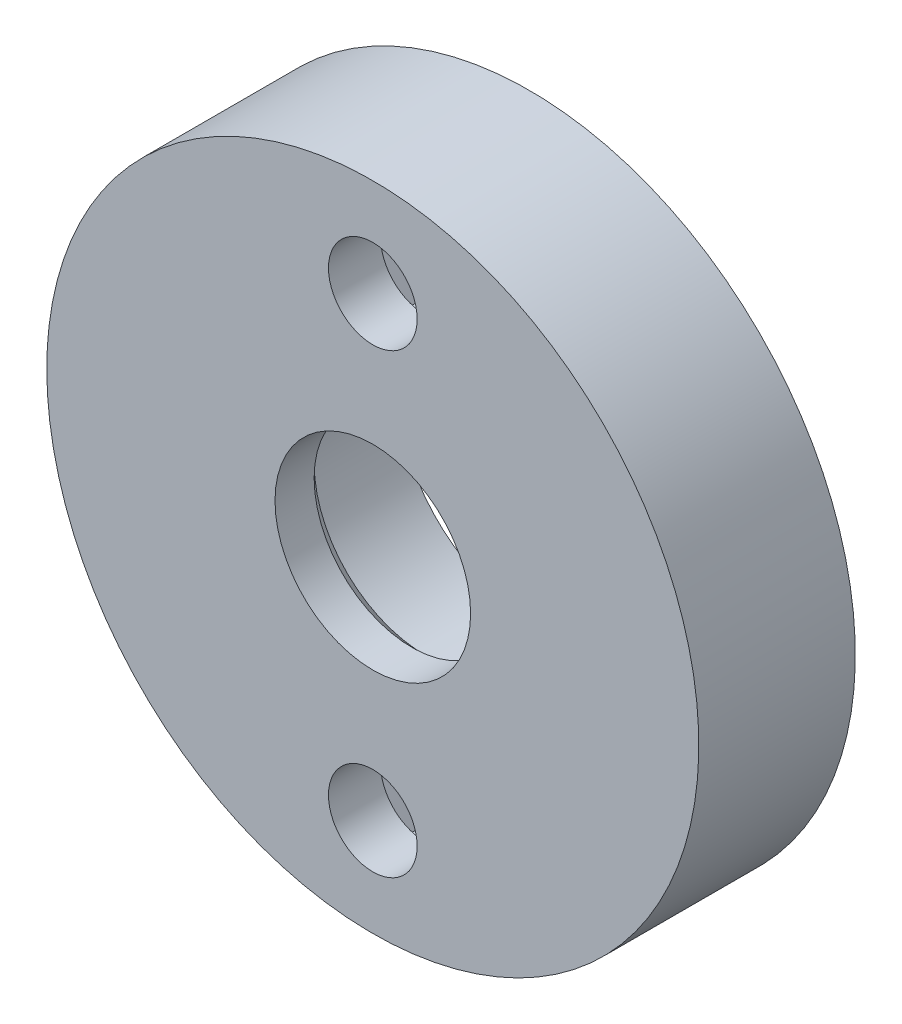
SolidWorks part; units mm, degrees
ref_plane "Plan de face" through (0, 0, 0) normal (0, 0, 1) x (1, 0, 0)
ref_plane "Plan de dessus" through (0, 0, 0) normal (0, 1, 0) x (1, 0, 0)
ref_plane "Plan de droite" through (0, 0, 0) normal (1, 0, 0) x (0, 0, -1)
sketch "Esquisse1" plane through (0, 0, 0) normal (0, 0, 1) x (1, 0, 0)
  line L0 (0, 12.5) -> (0, 0) construction
  ellipse E0 centre (0, 0) end of major axis (12.5, 0) minor radius 12.5
  dimension "D1" = 25
  dimension "D2" = 25
extrude "Boss.-Extru.1" add sketch "Esquisse1" along normal blind 6
sketch "Esquisse2" plane through (0, 0, 0) normal (0, 0, -1) x (-1, 0, 0)
  circle A0 centre (0, 0) radius 5
  dimension "D1" = 10
extrude "Enlèv. mat.-Extru.1" cut sketch "Esquisse2" against normal blind 4
sketch "Esquisse3" plane through (0, 0, 4) normal (0, 0, -1) x (-1, 0, 0)
  circle A0 centre (0, 0) radius 3.75
  dimension "D1" = 7.5
extrude "Enlèv. mat.-Extru.2" cut sketch "Esquisse3" against normal up to next
chamfer "Chanfrein1" distance 0.5 angle 45 1 edges at (-3.75, 0, 4)
sketch "Esquisse5" plane through (0, 0, 0) normal (0, 0, -1) x (-1, 0, 0)
  line L0 (0, 5) -> (0, 12.5) construction
  line L1 (-3.1177, -8.75) -> (-1.5588, -11.45)
  line L2 (3.1177, 8.75) -> (1.5588, 11.45)
  line L3 (1.5588, 11.45) -> (-1.5588, 11.45)
  line L4 (-1.5588, 11.45) -> (-3.1177, 8.75)
  line L5 (-3.1177, 8.75) -> (-1.5588, 6.05)
  line L6 (-1.5588, 6.05) -> (1.5588, 6.05)
  line L7 (1.5588, 6.05) -> (3.1177, 8.75)
  line L8 (-1.5588, -11.45) -> (1.5588, -11.45)
  line L9 (1.5588, -11.45) -> (3.1177, -8.75)
  line L10 (3.1177, -8.75) -> (1.5588, -6.05)
  line L11 (1.5588, -6.05) -> (-1.5588, -6.05)
  line L12 (-1.5588, -6.05) -> (-3.1177, -8.75)
  circle A1 centre (0, 0) radius 5 construction
  circle A2 centre (0, 0) radius 5 construction
  circle A3 centre (0, 0) radius 12.5 construction
  circle A4 centre (0, 8.75) radius 2.7 construction
  point P1 (-1.8369, -0.4622)
  point P11 (-5, -10.3046)
  point P20 (-1.3589, -11.4754)
  point P27 (0, 0)
  dimension "D1" = 5.4
  dimension "D2" = 2
extrude "Enlèv. mat.-Extru.3" cut sketch "Esquisse5" against normal blind 4
sketch "Esquisse6" plane through (0, 0, 4) normal (0, 0, -1) x (-1, 0, 0)
  line L0 (1.5588, 11.45) -> (-1.5588, 11.45) construction
  line L1 (3.1177, 8.75) -> (1.5588, 11.45) construction
  line L2 (-3.1177, 8.75) -> (-1.5588, 6.05) construction
  line L3 (0, -8.75) -> (0, 0) construction
  circle A0 centre (0, 8.75) radius 1.7
  circle A1 centre (0, 8.75) radius 2.7 construction
  circle A2 centre (0, -8.75) radius 1.7
  point P14 (0, 0)
  dimension "D1" = 3.4
  dimension "D2" = 2
extrude "Enlèv. mat.-Extru.4" cut sketch "Esquisse6" against normal up to next
